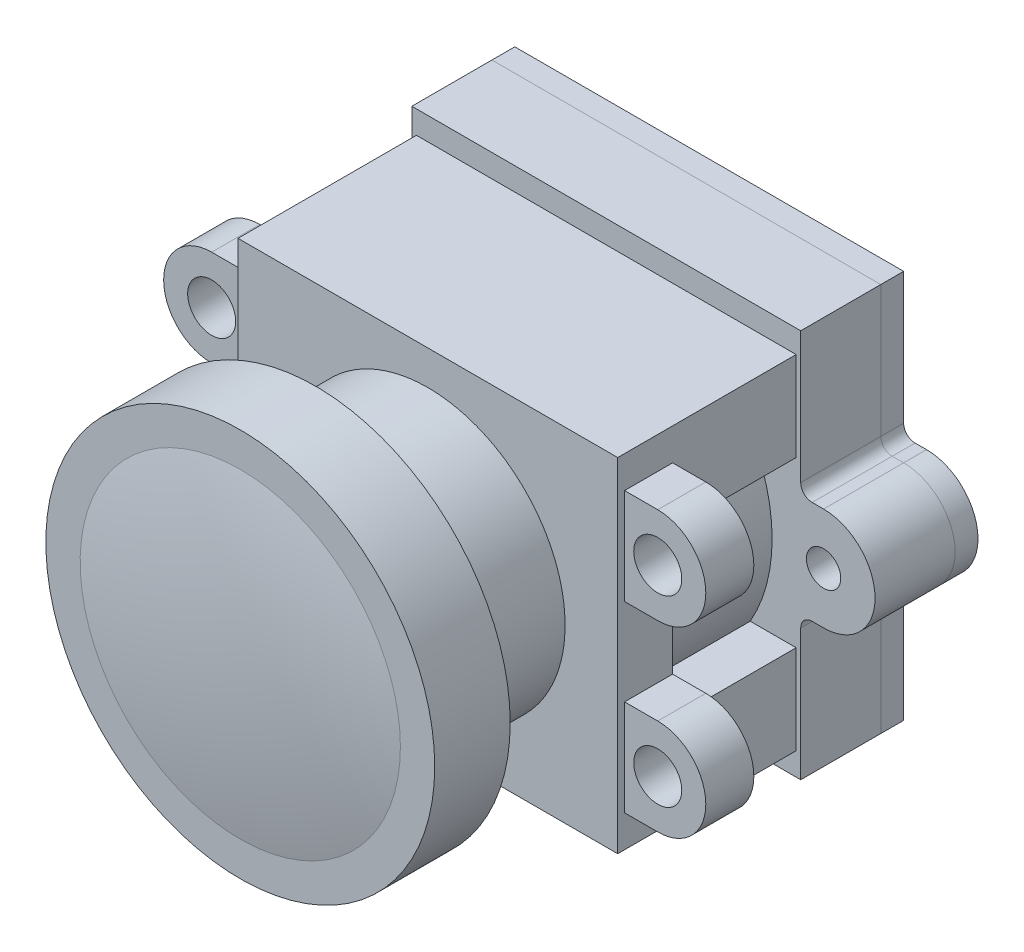
SolidWorks part; units mm, degrees
material "Винипласт"
ref_plane "Спереди" through (0, 0, 0) normal (0, 0, 1) x (1, 0, 0)
ref_plane "Сверху" through (0, 0, 0) normal (0, 1, 0) x (1, 0, 0)
ref_plane "Справа" through (0, 0, 0) normal (1, 0, 0) x (0, 0, -1)
sketch "Эскиз1" plane through (0, 0, 0) normal (1, 0, 0) x (0, 0, -1)
  line L0 (0, 6) -> (0, 8.5)
  line L1 (0, 8.5) -> (-3.3, 8.5)
  line L2 (-3.3, 8.5) -> (-3.3, 7)
  line L3 (0, 0) -> (15.9473, 0)
  line L4 (0, 6) -> (10, 6)
  line L5 (-4, 0) -> (-4, 7.119) construction
  line L6 (-4, 0) -> (0, 0) construction
  line L7 (10, 6) -> (10, 0)
  line L8 (-4, 0) -> (0, 0)
  arc A0 (-3.3, 7) -> (-4, 0) centre (31.35, 0) ccw
  dimension "D1" = 17
  dimension "D2" = 14
  dimension "D3" = 3.3
  dimension "D4" = 4
  dimension "D5" = 12
  dimension "D6" = 10
revolve "Повернуть1" add sketch "Эскиз1" angle 360 about L6
sketch "Эскиз2" plane through (0, 0, -10) normal (0, 0, -1) x (-1, 0, 0)
  line L1 (-8.3, -7.5) -> (8.3, -7.5)
  line L2 (-8.3, -7.5) -> (-8.3, 7.5)
  line L3 (-8.3, 7.5) -> (8.3, 7.5)
  line L4 (8.3, -7.5) -> (8.3, 7.5)
  line L5 (-8.3, -7.5) -> (8.3, 7.5) construction
  line L6 (-8.3, 7.5) -> (8.3, -7.5) construction
  circle A0 centre (0, 0) radius 6
  point P0 (0, 0)
  dimension "D3" = 12
  dimension "D1" = 15
  dimension "D2" = 16.6
extrude "Бобышка-Вытянуть1" add sketch "Эскиз2" along normal blind 7.8 from offset 5.1 separate body offset against normal yes
sketch "Эскиз3" plane through (0, 0, -4.9) normal (0, 0, 1) x (1, 0, 0)
  line L0 (-9.75, 6.1) -> (-8.3, 6.1)
  line L1 (-8.3, -7.5) -> (-8.3, 7.5) construction
  line L2 (-9.75, 1.9) -> (-8.3, 1.9)
  line L3 (0, 0) -> (-14.3156, 0) construction
  line L4 (0, -8.9633) -> (0, 8.9633) construction
  line L5 (-11.85, 4) -> (-11.85, 7.5508) construction
  line L6 (-9.75, 6.1) -> (-9.75, 5.05) construction
  line L7 (9.75, 6.1) -> (9.75, 5.05) construction
  line L8 (11.85, 4) -> (11.85, 7.5508) construction
  line L9 (9.75, 1.9) -> (8.3, 1.9)
  line L10 (9.75, 6.1) -> (8.3, 6.1)
  line L11 (11.85, -4) -> (11.85, -7.5508) construction
  line L12 (9.75, -6.1) -> (9.75, -5.05) construction
  line L13 (-9.75, -6.1) -> (-9.75, -5.05) construction
  line L14 (-11.85, -4) -> (-11.85, -7.5508) construction
  line L15 (9.75, -6.1) -> (8.3, -6.1)
  line L16 (9.75, -1.9) -> (8.3, -1.9)
  line L17 (-9.75, -1.9) -> (-8.3, -1.9)
  line L18 (-9.75, -6.1) -> (-8.3, -6.1)
  line L19 (-8.3, 6.1) -> (-8.3, 1.9)
  line L20 (-8.3, -1.9) -> (-8.3, -6.1)
  line L21 (8.3, -6.1) -> (8.3, -1.9)
  line L22 (8.3, 6.1) -> (8.3, 1.9)
  circle A0 centre (-9.75, 4) radius 1.05
  arc A1 (-9.75, 6.1) -> (-9.75, 1.9) centre (-9.75, 4) ccw
  arc A2 (9.75, 6.1) -> (9.75, 1.9) centre (9.75, 4) cw
  circle A3 centre (9.75, 4) radius 1.05
  circle A4 centre (9.75, -4) radius 1.05
  arc A5 (9.75, -6.1) -> (9.75, -1.9) centre (9.75, -4) ccw
  arc A6 (-9.75, -6.1) -> (-9.75, -1.9) centre (-9.75, -4) cw
  circle A7 centre (-9.75, -4) radius 1.05
  dimension "D1" = 4.2
  dimension "D3" = 2.1
  dimension "D4" = 19.5
  dimension "D2" = 8
  dimension "D5" = 3.55
extrude "Бобышка-Вытянуть2" add sketch "Эскиз3" against normal blind 2.1 from offset 0.3 offset against normal yes
sketch "Эскиз4" plane through (0, 0, -12.7) normal (0, 0, -1) x (-1, 0, 0)
  line L0 (9.5, 0) -> (-9.5, 0) construction
  line L1 (-8.5, -8.5) -> (8.5, -8.5)
  line L2 (-8.5, -8.5) -> (-8.5, -2.75)
  line L3 (-8.5, 8.5) -> (8.5, 8.5)
  line L4 (8.5, -8.5) -> (8.5, -2.75)
  line L5 (-8.5, -8.5) -> (8.5, 8.5) construction
  line L6 (-8.5, 8.5) -> (8.5, -8.5) construction
  line L7 (-9.5, 2.25) -> (-9, 2.25)
  line L8 (-9.5, -2.25) -> (-9, -2.25)
  line L9 (-8.5, 2.75) -> (-8.5, 8.5)
  line L10 (0, 0) -> (0, 8.5) construction
  line L11 (9.5, -2.25) -> (9, -2.25)
  line L12 (9.5, 2.25) -> (9, 2.25)
  line L13 (-11.75, 0) -> (-11.75, 3.6029) construction
  line L14 (11.75, 0) -> (11.75, 2.0444) construction
  line L15 (8.5, 2.75) -> (8.5, 8.5)
  arc A0 (-9.5, 2.25) -> (-9.5, -2.25) centre (-9.5, 0) ccw
  circle A1 centre (-9.5, 0) radius 0.75
  arc A2 (-9, 2.25) -> (-8.5, 2.75) centre (-9, 2.75) ccw
  arc A3 (-9, -2.25) -> (-8.5, -2.75) centre (-9, -2.75) cw
  arc A4 (9, -2.25) -> (8.5, -2.75) centre (9, -2.75) ccw
  arc A5 (9, 2.25) -> (8.5, 2.75) centre (9, 2.75) cw
  circle A6 centre (9.5, 0) radius 0.75
  arc A7 (9.5, 2.25) -> (9.5, -2.25) centre (9.5, 0) cw
  point P0 (0, 0)
  point P16 (-8.5, 2.25)
  dimension "D1" = 1.5
  dimension "D2" = 0.5
  dimension "D4" = 19
  dimension "D3" = 23.5
  dimension "D5" = 4.5
  dimension "D6" = 17
  dimension "D7" = 17
extrude "Бобышка-Вытянуть3" add sketch "Эскиз4" along normal blind 3.5
sketch "Эскиз5" plane through (0, 0, -16.2) normal (0, 0, -1) x (-1, 0, 0)
  line L10 (8.5, 2.75) -> (8.5, 8.5)
  line L11 (8.5, 8.5) -> (-8.5, 8.5)
  line L12 (-8.5, 8.5) -> (-8.5, 2.75)
  line L13 (-9, 2.25) -> (-9.5, 2.25)
  line L14 (-9.5, -2.25) -> (-9, -2.25)
  line L15 (-8.5, -2.75) -> (-8.5, -8.5)
  line L16 (-8.5, -8.5) -> (8.5, -8.5)
  line L17 (8.5, -8.5) -> (8.5, -2.75)
  line L18 (9, -2.25) -> (9.5, -2.25)
  line L19 (9.5, 2.25) -> (9, 2.25)
  line L20 (8.5, 2.75) -> (8.5, 8.5)
  line L21 (8.5, 8.5) -> (-8.5, 8.5)
  line L22 (-8.5, 8.5) -> (-8.5, 2.75)
  line L23 (-9, 2.25) -> (-9.5, 2.25)
  line L24 (-9.5, -2.25) -> (-9, -2.25)
  line L25 (-8.5, -2.75) -> (-8.5, -8.5)
  line L26 (-8.5, -8.5) -> (8.5, -8.5)
  line L27 (8.5, -8.5) -> (8.5, -2.75)
  line L28 (9, -2.25) -> (9.5, -2.25)
  line L29 (9.5, 2.25) -> (9, 2.25)
  circle A0 centre (9.5, 0) radius 0.75 construction
  circle A1 centre (-9.5, 0) radius 0.75 construction
  circle A2 centre (9.5, 0) radius 0.75
  circle A3 centre (-9.5, 0) radius 0.75
  arc A6 (-9, 2.25) -> (-8.5, 2.75) centre (-9, 2.75) ccw
  arc A7 (-9.5, 2.25) -> (-9.5, -2.25) centre (-9.5, 0) ccw
  arc A8 (-8.5, -2.75) -> (-9, -2.25) centre (-9, -2.75) ccw
  arc A9 (9, -2.25) -> (8.5, -2.75) centre (9, -2.75) ccw
  arc A10 (9.5, -2.25) -> (9.5, 2.25) centre (9.5, 0) ccw
  arc A11 (8.5, 2.75) -> (9, 2.25) centre (9, 2.75) ccw
  arc A12 (-9, 2.25) -> (-8.5, 2.75) centre (-9, 2.75) ccw
  arc A13 (-9.5, 2.25) -> (-9.5, -2.25) centre (-9.5, 0) ccw
  arc A14 (-8.5, -2.75) -> (-9, -2.25) centre (-9, -2.75) ccw
  arc A15 (9, -2.25) -> (8.5, -2.75) centre (9, -2.75) ccw
  arc A16 (9.5, -2.25) -> (9.5, 2.25) centre (9.5, 0) ccw
  arc A17 (8.5, 2.75) -> (9, 2.25) centre (9, 2.75) ccw
  dimension "D1" = 0
extrude "Бобышка-Вытянуть4" add sketch "Эскиз5" along normal blind 1 separate body
sketch "Эскиз7" plane through (0, 0, -12.7) normal (0, 0, 1) x (1, 0, 0)
  line L0 (-8.3, -3.6) -> (-8.3, 3.6)
  line L1 (-8.3, -3.6) -> (-6.2931, -3.6)
  line L2 (-8.3, -7.5) -> (-8.3, 7.5) construction
  line L3 (-8.3, 3.6) -> (-6.2931, 3.6)
  line L4 (8.3, 3.6) -> (6.2931, 3.6)
  line L5 (0, 0) -> (0, 3.4293) construction
  line L6 (8.3, -3.6) -> (6.2931, -3.6)
  line L7 (-9.5, 0) -> (9.5, 0) construction
  line L8 (8.3, -3.6) -> (8.3, 3.6)
  arc A0 (-6.2931, 3.6) -> (-6.2931, -3.6) centre (0, 0) ccw
  arc A2 (6.2931, 3.6) -> (6.2931, -3.6) centre (0, 0) cw
  point P15 (-8.3, 0)
  point P17 (8.3, 0)
  dimension "D1" = 7.25
  dimension "D2" = 7.2
extrude "Вырез-Вытянуть1" cut sketch "Эскиз7" along normal up to surface (5.4 mm away) up to face at (-8.7, 4, -7.3)
